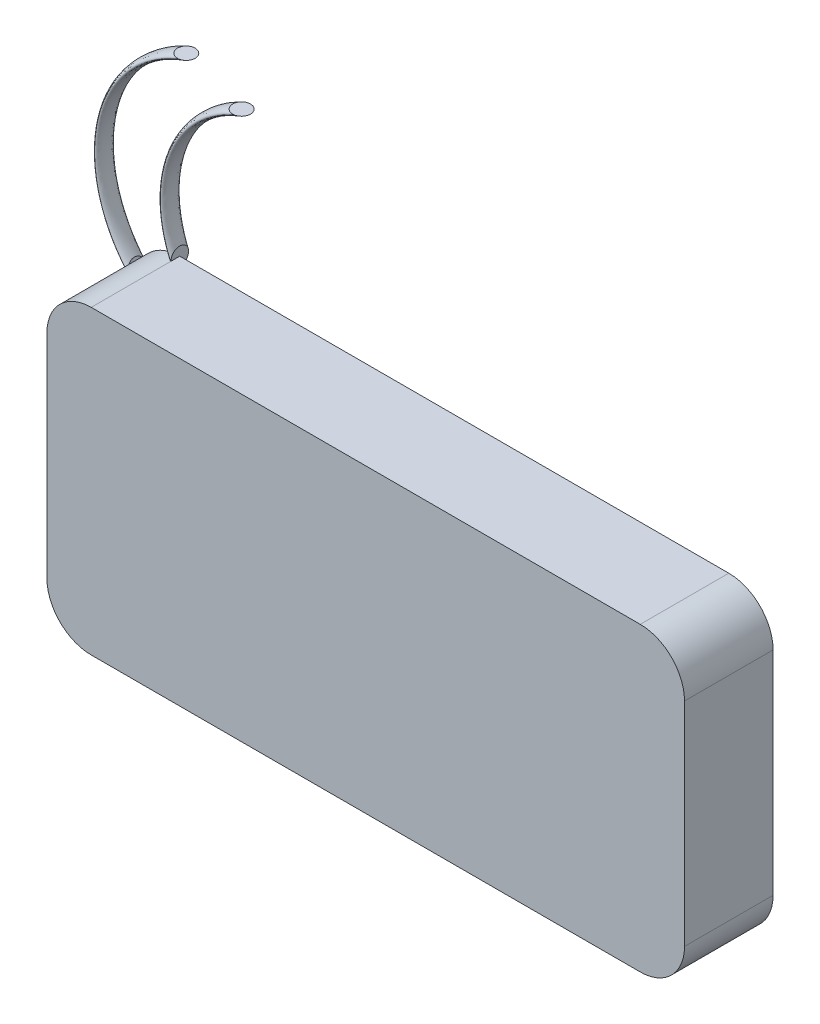
SolidWorks part; units mm, degrees
ref_plane "Alzado" through (0, 0, 0) normal (0, 0, 1) x (1, 0, 0)
ref_plane "Planta" through (0, 0, 0) normal (0, 1, 0) x (1, 0, 0)
ref_plane "Vista lateral" through (0, 0, 0) normal (1, 0, 0) x (0, 0, -1)
sketch "Croquis1" plane through (0, 0, 0) normal (0, 0, 1) x (1, 0, 0)
  line L1 (5, 0) -> (67, 0)
  line L2 (0, 5) -> (0, 29)
  line L3 (5, 34) -> (67, 34)
  line L4 (72, 5) -> (72, 29)
  arc A0 (67, 0) -> (72, 5) centre (67, 5) ccw
  arc A1 (67, 34) -> (72, 29) centre (67, 29) cw
  arc A2 (0, 29) -> (5, 34) centre (5, 29) cw
  arc A3 (5, 0) -> (0, 5) centre (5, 5) cw
  point P7 (72, 0)
  point P12 (0, 34)
  point P15 (0, 0)
  dimension "D3" = 5
  dimension "D1" = 34
  dimension "D2" = 72
extrude "Saliente-Extruir1" add sketch "Croquis1" along normal blind 10
sketch "Croquis3" plane through (0, 0, 0) normal (0, 0, -1) x (-1, 0, 0)
  arc A1 (0, 29) -> (-5, 34) centre (-5, 29) ccw construction
  arc A2 (-0.2053, 30.418) -> (-5.7404, 54.2185) centre (-11.425, 40.3526) ccw
ref_plane "Plano1" through (0, 54.2185, 0) normal (0, 1, 0) x (1, 0, 0)
sketch "Croquis4" plane through (0, 54.2185, 0) normal (0, 1, 0) x (1, 0, 0)
  circle A0 centre (5.7351, 0) radius 1
  dimension "D1" = 2
sweep "Barrer1" add profiles "Croquis4" path "Croquis3"
sketch "Croquis6" plane through (0, 0, 0) normal (0, 0, -1) x (-1, 0, 0)
  arc A0 (-5, 34) -> (-11.9857, 51.8851) centre (-17.4354, 39.4497) ccw
ref_plane "Plano3" through (0, 51.8851, 0) normal (0, 1, 0) x (1, 0, 0)
sketch "Croquis7" plane through (0, 51.8851, 0) normal (0, 1, 0) x (1, 0, 0)
  circle A0 centre (11.9857, 0) radius 0.9991
  dimension "D1" = 1.9982
sweep "Barrer4" add profiles "Croquis7" path "Croquis6"
